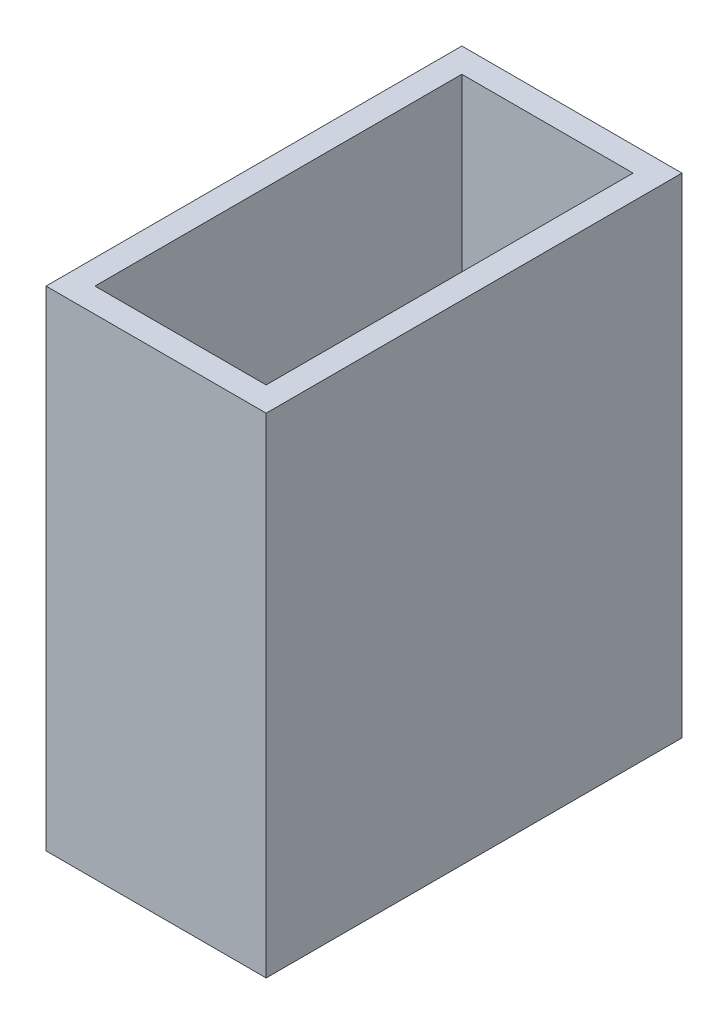
SolidWorks part; units mm, degrees
ref_plane "Front Plane" through (0, 0, 0) normal (0, 0, 1) x (1, 0, 0)
ref_plane "Top Plane" through (0, 0, 0) normal (0, 1, 0) x (1, 0, 0)
ref_plane "Right Plane" through (0, 0, 0) normal (1, 0, 0) x (0, 0, -1)
sketch "Sketch1" plane through (0, 0, 0) normal (0, 1, 0) x (1, 0, 0)
  line L1 (-22.5, 42.5) -> (22.5, 42.5)
  line L2 (-22.5, 42.5) -> (-22.5, -42.5)
  line L3 (-22.5, -42.5) -> (22.5, -42.5)
  line L4 (22.5, 42.5) -> (22.5, -42.5)
  line L5 (-22.5, 42.5) -> (22.5, -42.5) construction
  line L6 (-22.5, -42.5) -> (22.5, 42.5) construction
  point P0 (0, 0)
  dimension "D1" = 45
  dimension "D2" = 85
extrude "Boss-Extrude1" add sketch "Sketch1" along normal blind 100
shell "Shell1" thickness 5
sketch "Sketch2" plane through (0, 5, 0) normal (0, 1, 0) x (1, 0, 0)
  line L0 (-13.25, 0) -> (-13.25, -29)
  line L1 (-13.25, -29) -> (-1.25, -29)
  line L2 (-1.25, -29) -> (-1.25, -13.1909)
  line L3 (-16.25, 0) -> (-16.25, -32)
  line L4 (-16.25, -32) -> (1.75, -32)
  line L5 (1.75, -32) -> (1.75, -13.1339)
  line L6 (-13.25, 0) -> (-16.25, 0)
  line L7 (3.4294, 12.7985) -> (4.2058, 15.6963)
  line L8 (-4.2058, 15.6963) -> (-3.4294, 12.7985)
  line L9 (-1.25, -16.2019) -> (-1.25, -13.1909)
  line L10 (-1.25, -29) -> (-1.25, -12.0576) construction
  line L11 (1.75, -32) -> (1.75, -12.0576) construction
  line L12 (1.75, -16.1555) -> (1.75, -13.1339)
  line L13 (-1.25, -16.2019) -> (-1.25, -13.1909)
  line L14 (1.75, -13.1339) -> (1.75, -16.1555)
  line L19 (-1.25, -13.1909) -> (-1.25, -16.2019)
  line L20 (-13.25, -24) -> (-16.25, -24)
  line L21 (-16.25, -14) -> (-13.25, -14)
  circle A1 centre (0, 0) radius 16.25
  circle A2 centre (0, 0) radius 13.25
  arc A3 (1.75, -16.1555) -> (-1.25, -16.2019) centre (0, 0) cw
  arc A4 (1.75, -13.1339) -> (-1.25, -13.1909) centre (0, 0) cw
  dimension "D1" = 26.5
  dimension "D2" = 32.5
  dimension "D3" = 12
  dimension "D4" = 30
  dimension "D6" = 15
  dimension "D7" = 29
  dimension "D8" = 10
  dimension "D9" = 8
  dimension "D5" = 3
extrude "Boss-Extrude2" add sketch "Sketch2" along normal blind 15 contours A1 L2 L1 L0 L20 L3 L4 L5 | L21 L3 L20 L0 | A1 L3 L21 L0 | A2 L7 A1 L8 | L6 A1 L0 | A2 L2 A1 L5
sketch "Sketch4" plane through (-13.25, 0, 0) normal (1, 0, 0) x (0, 0, -1)
  line L0 (0, 5) -> (-29, 5) construction
  line L1 (-29, 20) -> (-9, 20)
  line L2 (-29, 20) -> (-29, 17.5)
  line L3 (-29, 17.5) -> (-9, 17.5)
  line L4 (-9, 20) -> (-9, 17.5)
  dimension "D1" = 12.5
  dimension "D2" = 20
extrude "Boss-Extrude3" add sketch "Sketch4" along normal blind 1
sketch "Sketch5" plane through (-1.25, 0, 0) normal (-1, 0, 0) x (0, 0, 1)
  line L6 (29, 20) -> (29, 5) construction
  line L7 (13.1909, 20) -> (29, 20)
  line L8 (13.1909, 20) -> (13.1909, 18)
  line L9 (13.1909, 18) -> (29, 18)
  line L10 (29, 20) -> (29, 18)
  dimension "D1" = 2
extrude "Boss-Extrude4" add sketch "Sketch5" along normal blind 1
sketch "Sketch6" plane through (0, 0, 29) normal (0, 0, -1) x (-1, 0, 0)
  line L2 (12.25, 17.5) -> (2.25, 17.5)
  line L3 (12.25, 17.5) -> (12.25, 20)
  line L4 (12.25, 20) -> (2.25, 20)
  line L5 (2.25, 17.5) -> (2.25, 20)
extrude "Boss-Extrude5" add sketch "Sketch6" along normal blind 1
sketch "Sketch9" plane through (0, 20, 0) normal (0, 1, 0) x (1, 0, 0)
  line L1 (-5.0753, 17.3777) -> (5.4023, 17.3777)
  line L2 (-5.0753, 17.3777) -> (-5.0753, 11.055)
  line L3 (-5.0753, 11.055) -> (5.4023, 11.055)
  line L4 (5.4023, 17.3777) -> (5.4023, 11.055)
extrude "Cut-Extrude1" cut sketch "Sketch9" against normal blind 9
